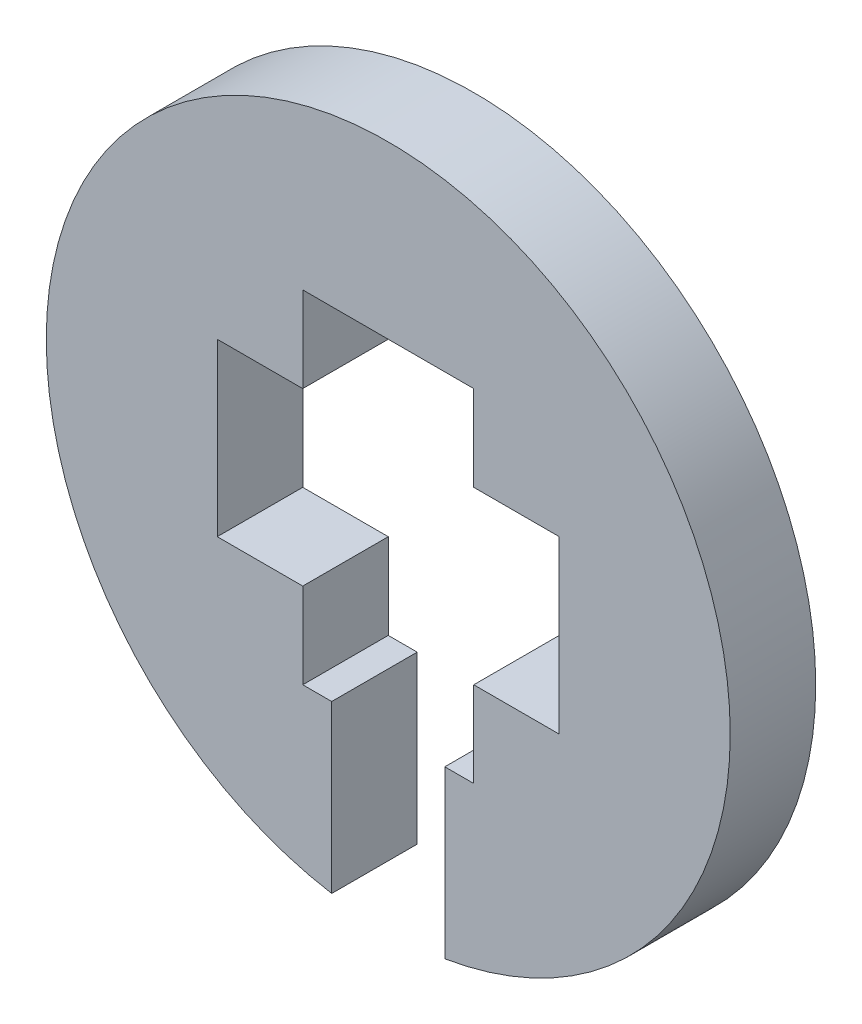
SolidWorks part; units mm, degrees
ref_plane "Front Plane" through (0, 0, 0) normal (0, 0, 1) x (1, 0, 0)
ref_plane "Top Plane" through (0, 0, 0) normal (0, 1, 0) x (1, 0, 0)
ref_plane "Right Plane" through (0, 0, 0) normal (1, 0, 0) x (0, 0, -1)
sketch "Sketch1" plane through (0, 0, 0) normal (0, 0, 1) x (1, 0, 0)
  line L0 (0, 0) -> (0, 3.175) construction
  line L1 (0, 0) -> (-3.175, 0) construction
  line L2 (-3.175, -1.5875) -> (-3.175, 1.5875)
  line L3 (-3.175, 1.5875) -> (-1.5875, 1.5875)
  line L4 (-1.5875, 1.5875) -> (-1.5875, 3.175)
  line L5 (-1.5875, 3.175) -> (1.5875, 3.175)
  line L6 (-1.5875, -3.175) -> (1.5875, -3.175)
  line L7 (-1.5875, -1.5875) -> (-1.5875, -3.175)
  line L8 (-3.175, -1.5875) -> (-1.5875, -1.5875)
  line L9 (3.175, -1.5875) -> (1.5875, -1.5875)
  line L10 (1.5875, -1.5875) -> (1.5875, -3.175)
  line L11 (1.5875, 1.5875) -> (1.5875, 3.175)
  line L12 (3.175, 1.5875) -> (1.5875, 1.5875)
  line L13 (3.175, -1.5875) -> (3.175, 1.5875)
  circle A0 centre (0, 0) radius 6.35
  point P15 (0, -3.175)
  dimension "D1" = 12.7
  dimension "D2" = 6.35
  dimension "D3" = 1.5875
  dimension "D4" = 1.5875
  dimension "D5" = 1.5875
extrude "Boss-Extrude1" add sketch "Sketch1" along normal blind 1.5875
sketch "Sketch2" plane through (0, 0, 0) normal (0, 0, -1) x (-1, 0, 0)
  line L0 (0, 0) -> (0, -6.35) construction
  line L1 (1.5875, -3.175) -> (-1.5875, -3.175) construction
  line L2 (-1.05, -6.35) -> (1.05, -6.35)
  line L3 (-1.05, -6.35) -> (-1.05, -3.175)
  line L4 (-1.05, -3.175) -> (1.05, -3.175)
  line L5 (1.05, -6.35) -> (1.05, -3.175)
  circle A0 centre (0, 0) radius 6.35 construction
  dimension "D1" = 2.1
extrude "Cut-Extrude1" cut sketch "Sketch2" against normal through all
